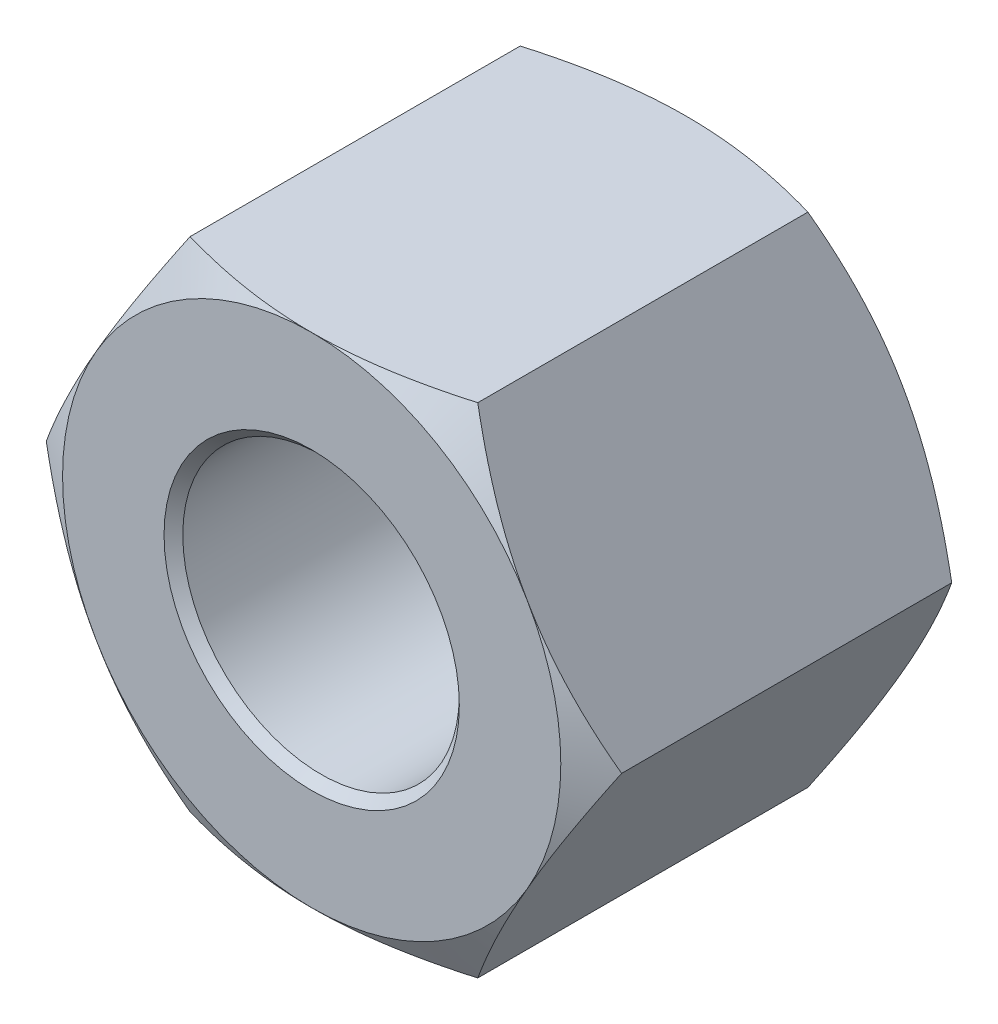
SolidWorks part; units mm, degrees
ref_plane "基准面1" through (0, 0, 0) normal (0, 0, 1) x (1, 0, 0)
ref_plane "基准面2" through (0, 0, 0) normal (0, 1, 0) x (1, 0, 0)
ref_plane "基准面3" through (0, 0, 0) normal (1, 0, 0) x (0, 0, -1)
sketch "尺寸草图" plane through (0, 0, 0) normal (0, 0, 1) x (1, 0, 0)
  line L0 (0, 0) -> (8, 0) construction
  point P1 (6.7, 0)
  point P3 (5, 0)
  point P4 (0.8, 0)
  point P5 (8.6, 0)
  point P6 (5.6, 0)
  point P8 (8, 0)
  dimension "D" = 5
  dimension "e(最小)" = 8.6
  dimension "m(最大)" = 5.6
  dimension "s(公称)" = 8
  dimension "dw(最小)" = 6.7
  dimension "P" = 0.8
sketch "草图1" plane through (0, 0, 0) normal (0, 0, 1) x (1, 0, 0)
  line L0 (-26.8088, 0) -> (37.1748, 0) construction
  line L1 (0, 25.0215) -> (0, -25.0215) construction
  line L3 (2.15, 3.7239) -> (-2.15, 3.7239)
  line L4 (-2.15, 3.7239) -> (-4.3, 0)
  line L5 (-4.3, 0) -> (-2.15, -3.7239)
  line L6 (-2.15, -3.7239) -> (2.15, -3.7239)
  line L7 (2.15, -3.7239) -> (4.3, 0)
  line L8 (4.3, 0) -> (2.15, 3.7239)
  circle A0 centre (0, 0) radius 3.7239 construction
  circle A1 centre (0, 0) radius 2.067
  dimension "D" = 4.134
  dimension "e" = 8.6
extrude "基体-拉伸" add sketch "草图1" along normal blind 5.6
sketch "草图2" plane through (0, 0, 0) normal (0, 0, -1) x (-1, 0, 0)
  line L0 (-2.15, 3.7239) -> (2.15, 3.7239) construction
  circle A0 centre (0, 0) radius 3.7239
  circle A1 centre (0, 0) radius 2.067 construction
extrude "切除-拉伸1" cut sketch "草图2" against normal through all draft 60 flip side to cut
sketch "草图3" plane through (0, 0, 5.6) normal (0, 0, 1) x (1, 0, 0)
  line L0 (4.3, 0) -> (2.15, 3.7239) construction
  circle A0 centre (0, 0) radius 3.7239
extrude "切除-拉伸2" cut sketch "草图3" against normal through all draft 60 flip side to cut
chamfer "倒角1" distance 0.14 angle 45 2 edges at (2.067, 0, 0) (2.067, 0, 5.6)
